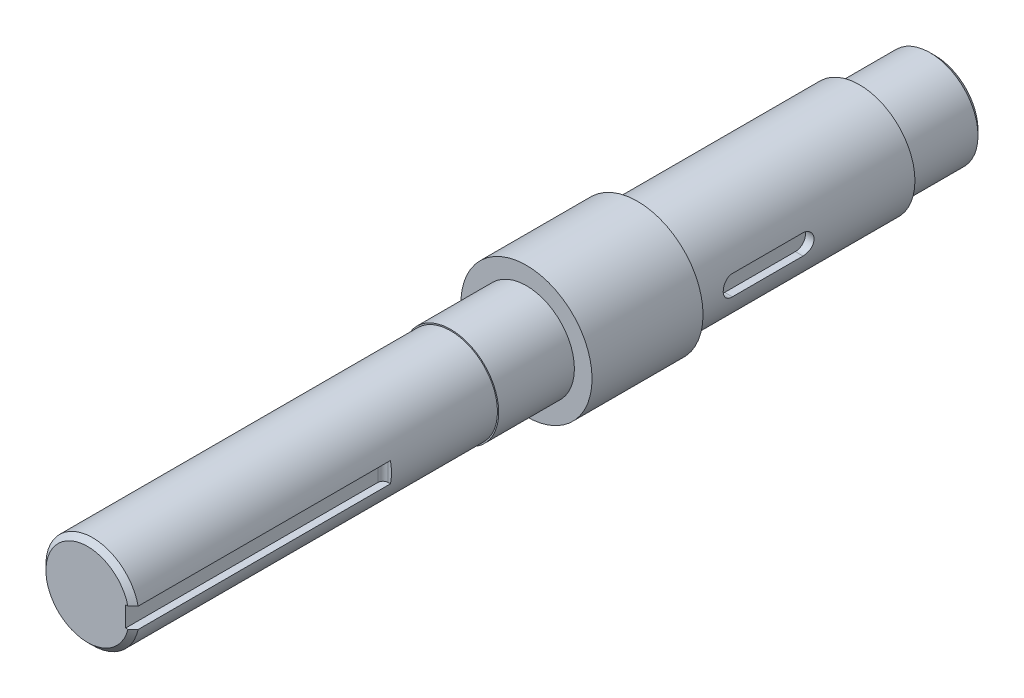
SolidWorks part; units mm, degrees
ref_plane "Front Plane" through (0, 0, 0) normal (0, 0, 1) x (1, 0, 0)
ref_plane "Top Plane" through (0, 0, 0) normal (0, 1, 0) x (1, 0, 0)
ref_plane "Right Plane" through (0, 0, 0) normal (1, 0, 0) x (0, 0, -1)
sketch "Sketch2" plane through (0, 0, 0) normal (0, 1, 0) x (1, 0, 0)
  line L0 (0, 0) -> (0, 168) construction
  line L1 (0, 0) -> (-9.25, 0)
  line L2 (-9.25, 0) -> (-9.25, 72)
  line L3 (-9.25, 72) -> (-9.5, 72)
  line L4 (-9.5, 72) -> (-9.5, 87)
  line L5 (-9.5, 87) -> (-13, 87)
  line L6 (-13, 87) -> (-13, 109)
  line L7 (-13, 109) -> (-11, 109)
  line L8 (-11, 109) -> (-11, 153)
  line L9 (-11, 153) -> (-9.5, 153)
  line L10 (-9.5, 153) -> (-9.5, 168)
  line L11 (-9.5, 168) -> (0, 168)
  line L12 (0, 0) -> (0, 168)
  dimension "D1" = 9.5
  dimension "D2" = 15
  dimension "D3" = 11
  dimension "D4" = 13
  dimension "D5" = 9.25
  dimension "D6" = 9.5
  dimension "D7" = 15
  dimension "D8" = 168
  dimension "D9" = 72
  dimension "D10" = 44
revolve "Revolve1" add sketch "Sketch2" angle 360 about L0
sketch "Sketch3" plane through (0, 0, 0) normal (0, 0, 1) x (1, 0, 0)
  line L1 (7.55, 2) -> (11.6297, 2)
  line L2 (7.55, 2) -> (7.55, -2)
  line L3 (7.55, -2) -> (11.6297, -2)
  line L4 (11.6297, 2) -> (11.6297, -2)
  circle A0 centre (0, 0) radius 9.25 construction
  circle A1 centre (0, 0) radius 9.25 construction
  point P4 (7.55, 0)
  point P5 (0, 0)
  point P12 (-9.25, 0)
  dimension "D1" = 4
  dimension "D2" = 16.8
extrude "Cut-Extrude1" cut sketch "Sketch3" against normal blind 51
sketch "Sketch4" plane through (0, 0, 0) normal (1, 0, 0) x (0, 0, -1)
  line L0 (109, -11) -> (109, 11) construction
  line L1 (117, 2) -> (131, 2)
  line L2 (117, 2) -> (117, -2) construction
  line L3 (117, -2) -> (131, -2)
  line L4 (131, 2) -> (131, -2) construction
  line L5 (117, 2) -> (131, -2) construction
  line L6 (117, -2) -> (131, 2) construction
  line L7 (109, -13) -> (109, 13) construction
  arc A0 (117, -2) -> (117, 2) centre (117, 0) cw
  arc A1 (131, -2) -> (131, 2) centre (131, 0) ccw
  point P0 (124, 0)
  point P13 (109, 0)
  dimension "D1" = 8
  dimension "D2" = 4
  dimension "D3" = 14
extrude "Cut-Extrude2" cut sketch "Sketch4" against normal blind 1.7 from offset 11
chamfer "Chamfer1" distance 1 angle 45 2 edges at (9.5, 0, -168) (-9.25, 0, 0)
fillet "Fillet1" radius 1 1 edges at (7.55, 0, -51)
